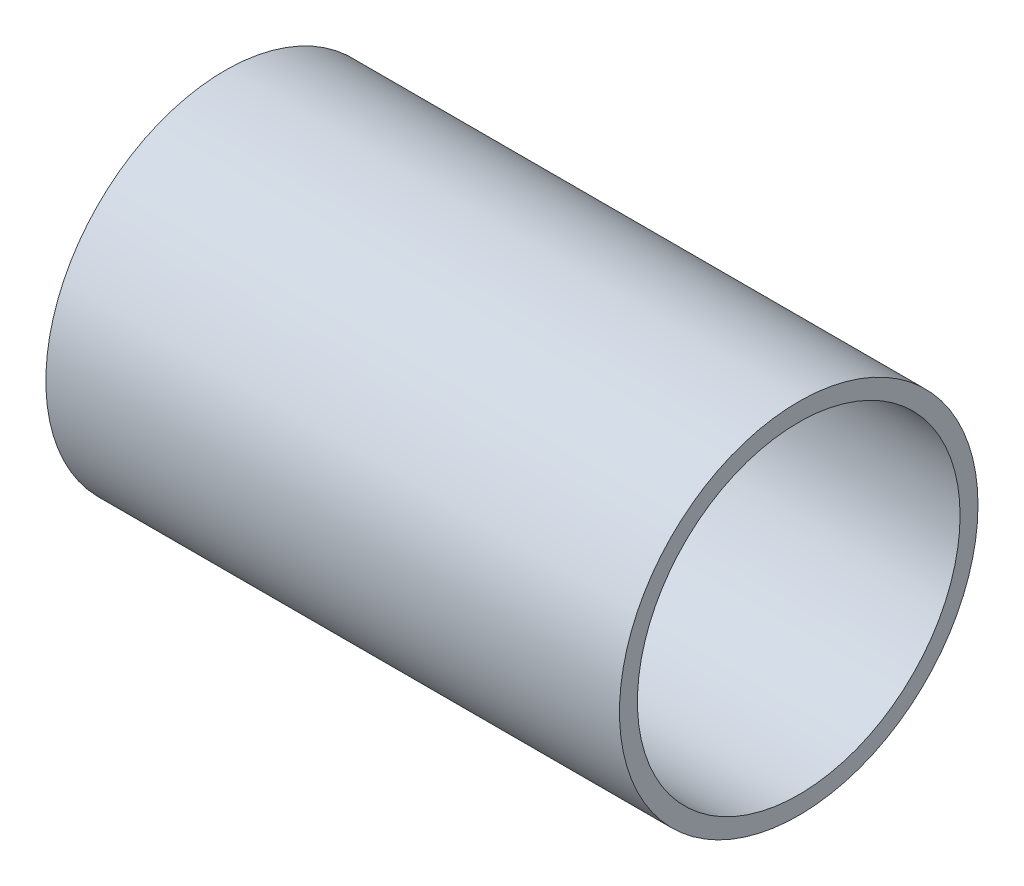
SolidWorks part; units mm, degrees
ref_plane "Front Plane" through (0, 0, 0) normal (0, 0, 1) x (1, 0, 0)
ref_plane "Top Plane" through (0, 0, 0) normal (0, 1, 0) x (1, 0, 0)
ref_plane "Right Plane" through (0, 0, 0) normal (1, 0, 0) x (0, 0, -1)
sketch "Sketch1" plane through (0, 0, 0) normal (1, 0, 0) x (0, 0, -1)
  circle A0 centre (0, 0) radius 14.2875
  circle A1 centre (0, 0) radius 15.875
extrude "Boss-Extrude1" add sketch "Sketch1" along normal mid plane 50.8
